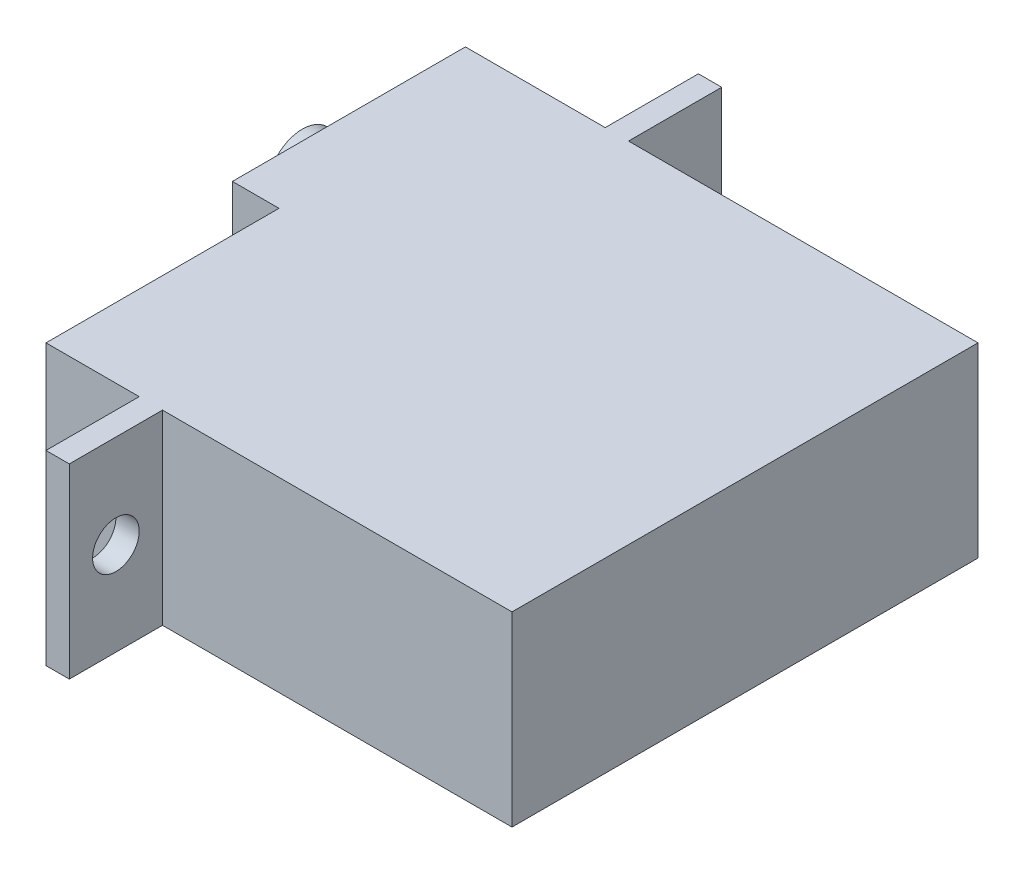
SolidWorks part; units mm, degrees
ref_plane "Front Plane" through (0, 0, 0) normal (0, 0, 1) x (1, 0, 0)
ref_plane "Top Plane" through (0, 0, 0) normal (0, 1, 0) x (1, 0, 0)
ref_plane "Right Plane" through (0, 0, 0) normal (1, 0, 0) x (0, 0, -1)
sketch "Sketch1" plane through (0, 0, 0) normal (0, 1, 0) x (1, 0, 0)
  line L1 (0, 0) -> (20, 0)
  line L2 (0, 0) -> (0, -20)
  line L3 (0, -20) -> (20, -20)
  line L4 (20, 0) -> (20, -20)
  dimension "D1" = 20
  dimension "D2" = 20
extrude "Boss-Extrude1" add sketch "Sketch1" along normal blind 8
sketch "Sketch2" plane through (0, 0, 0) normal (0, 0, -1) x (-1, 0, 0)
  line L0 (-20, 8) -> (0, 8) construction
  line L1 (-5, 8) -> (-4, 8)
  line L2 (-5, 8) -> (-5, 0)
  line L3 (-5, 0) -> (-4, 0)
  line L4 (-4, 8) -> (-4, 0)
  line L5 (-20, 0) -> (0, 0) construction
  line L6 (-20, 8) -> (-20, 0) construction
  dimension "D1" = 15
  dimension "D2" = 1
extrude "Boss-Extrude2" add sketch "Sketch2" along normal blind 4
sketch "Sketch3" plane through (0, 0, 20) normal (0, 0, 1) x (1, 0, 0)
  line L0 (0, 8) -> (20, 8) construction
  line L1 (4, 8) -> (5, 8)
  line L2 (4, 8) -> (4, 0)
  line L3 (4, 0) -> (5, 0)
  line L4 (5, 8) -> (5, 0)
  line L5 (0, 0) -> (20, 0) construction
  line L6 (20, 8) -> (20, 0) construction
  dimension "D1" = 1
  dimension "D2" = 15
extrude "Boss-Extrude3" add sketch "Sketch3" along normal blind 4
sketch "Sketch4" plane through (4, 0, 0) normal (-1, 0, 0) x (0, 0, 1)
  line L0 (-4, 8) -> (0, 0) construction
  line L1 (0, 0) -> (0, 8) construction
  line L2 (0, 8) -> (-4, 0) construction
  line L3 (20, 8) -> (24, 0) construction
  line L4 (24, 8) -> (20, 0) construction
  circle A0 centre (-2, 4) radius 1
  circle A1 centre (22, 4) radius 1
  point P21 (22, 4)
  dimension "D1" = 2
  dimension "D2" = 2
extrude "Cut-Extrude1" cut sketch "Sketch4" against normal blind 4
sketch "Sketch5" plane through (0, 0, 0) normal (-1, 0, 0) x (0, 0, 1)
  line L0 (0, 0) -> (20, 0) construction
  line L1 (0, 8) -> (10, 8)
  line L2 (0, 8) -> (0, 0)
  line L3 (0, 0) -> (10, 0)
  line L4 (10, 8) -> (10, 0)
  dimension "D1" = 10
extrude "Boss-Extrude4" add sketch "Sketch5" along normal blind 2
sketch "Sketch6" plane through (-2, 0, 0) normal (-1, 0, 0) x (0, 0, 1)
  line L0 (0, 0) -> (0, 8) construction
  circle A0 centre (4, 3.9446) radius 1.5
  dimension "D1" = 3
  dimension "D2" = 4
extrude "Boss-Extrude5" add sketch "Sketch6" along normal blind 3
